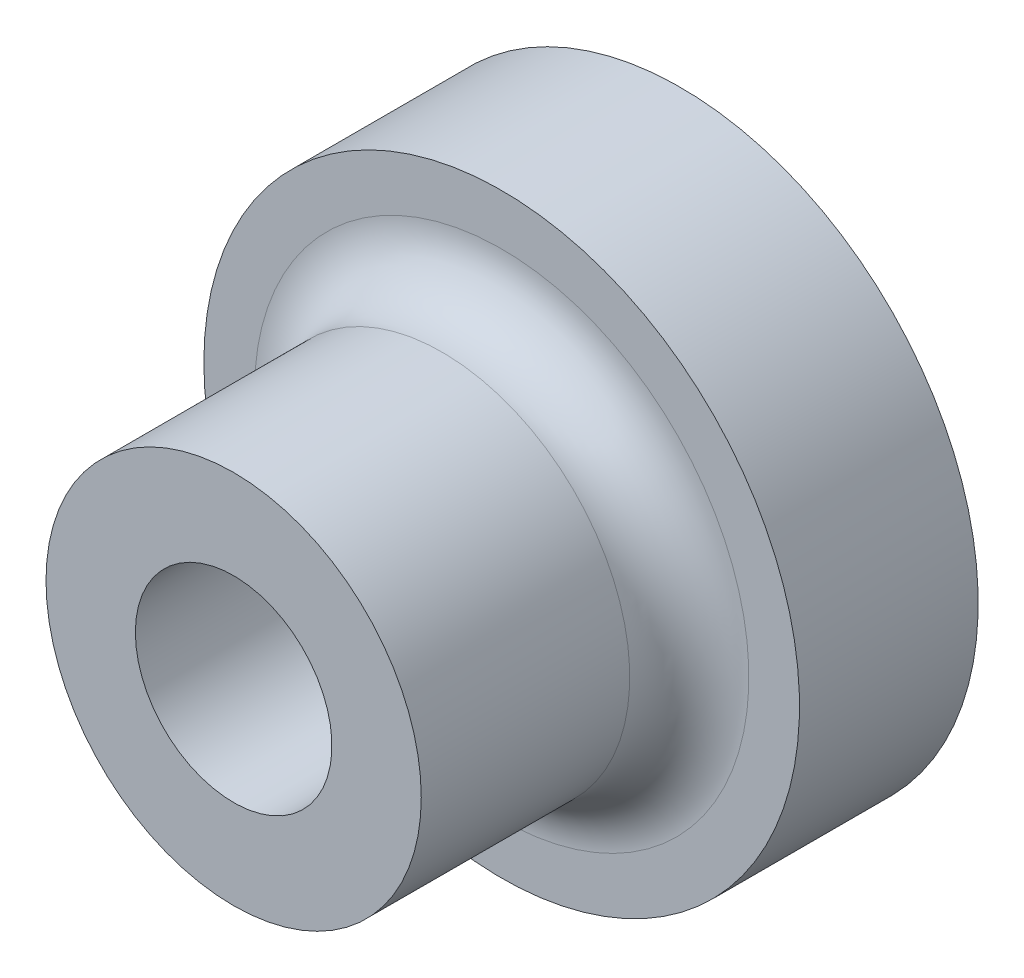
SolidWorks part; units mm, degrees
ref_plane "Plano frontal" through (0, 0, 0) normal (0, 0, 1) x (1, 0, 0)
ref_plane "Plano superior" through (0, 0, 0) normal (0, 1, 0) x (1, 0, 0)
ref_plane "Plano direito" through (0, 0, 0) normal (1, 0, 0) x (0, 0, -1)
sketch "Sketch1" plane through (0, 0, 0) normal (0, 0, 1) x (1, 0, 0)
  circle A0 centre (0, 0) radius 3.15
  dimension "D1" = 6.3
extrude "Boss-Extrude1" add sketch "Sketch1" along normal blind 4.5
sketch "Sketch2" plane through (0, 0, 0) normal (0, 0, -1) x (-1, 0, 0)
  circle A0 centre (0, 0) radius 5
  dimension "D1" = 10
extrude "Boss-Extrude2" add sketch "Sketch2" along normal blind 3
fillet "Fillet1" radius 1 1 edges at (3.15, 0, 0)
sketch "Sketch3" plane through (0, 0, -3) normal (0, 0, -1) x (-1, 0, 0)
  circle A0 centre (0, 0) radius 1.65
  dimension "D1" = 3.3
extrude "Cut-Extrude1" cut sketch "Sketch3" against normal up to next
